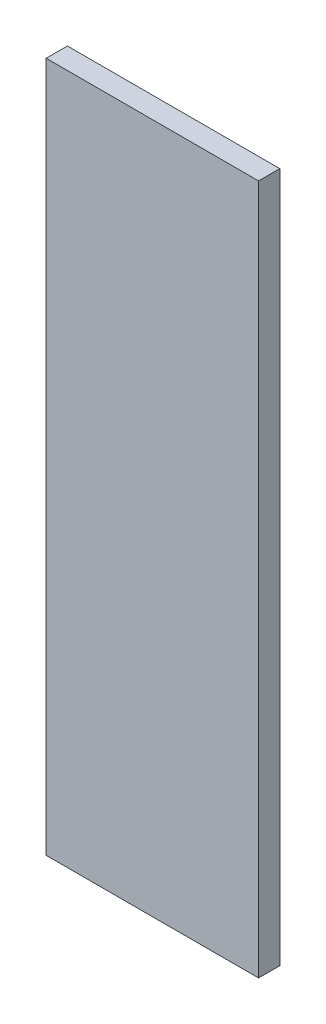
SolidWorks part; units mm, degrees
ref_plane "Front Plane" through (0, 0, 0) normal (0, 0, 1) x (1, 0, 0)
ref_plane "Top Plane" through (0, 0, 0) normal (0, 1, 0) x (1, 0, 0)
ref_plane "Right Plane" through (0, 0, 0) normal (1, 0, 0) x (0, 0, -1)
sketch "Sketch1" plane through (0, 0, 0) normal (0, 0, 1) x (1, 0, 0)
  line L1 (-40, -130) -> (40, -130)
  line L2 (-40, -130) -> (-40, 130)
  line L3 (-40, 130) -> (40, 130)
  line L4 (40, -130) -> (40, 130)
  line L5 (-40, -130) -> (40, 130) construction
  line L6 (-40, 130) -> (40, -130) construction
  point P0 (0, 0)
  dimension "D1" = 80
  dimension "D2" = 260
extrude "Boss-Extrude1" add sketch "Sketch1" along normal blind 8
